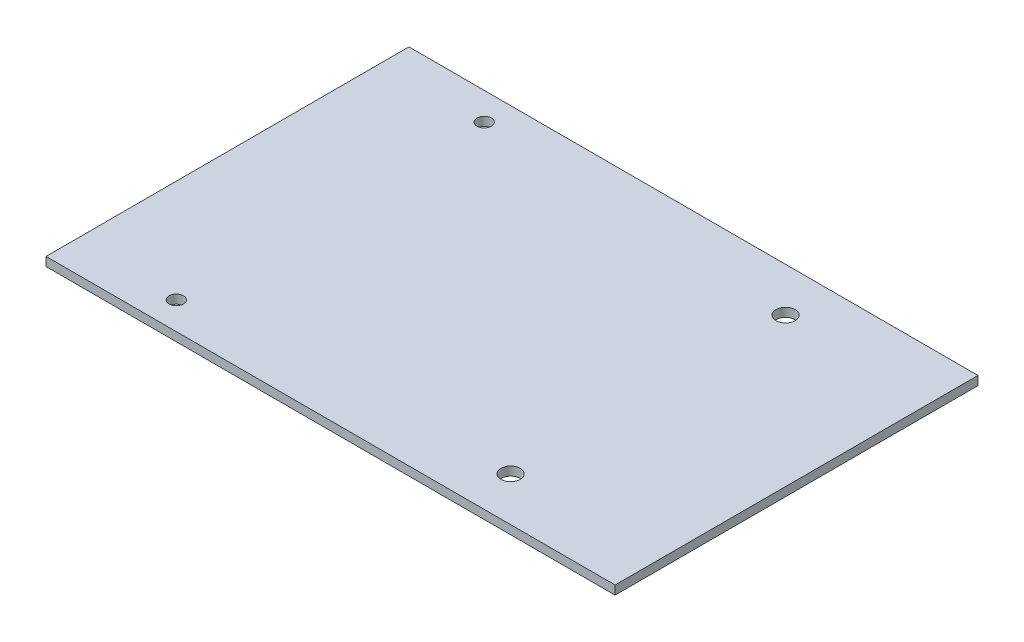
SolidWorks part; units mm, degrees
ref_plane "Front Plane" through (0, 0, 0) normal (0, 0, 1) x (1, 0, 0)
ref_plane "Top Plane" through (0, 0, 0) normal (0, 1, 0) x (1, 0, 0)
ref_plane "Right Plane" through (0, 0, 0) normal (1, 0, 0) x (0, 0, -1)
sketch "Sketch1" plane through (0, 0, 0) normal (0, 1, 0) x (1, 0, 0)
  line L1 (-51.75, -33) -> (51.75, -33)
  line L2 (-51.75, -33) -> (-51.75, 33)
  line L3 (-51.75, 33) -> (51.75, 33)
  line L4 (51.75, -33) -> (51.75, 33)
  line L5 (-51.75, -33) -> (51.75, 33) construction
  line L6 (-51.75, 33) -> (51.75, -33) construction
  point P0 (0, 0)
  dimension "D1" = 103.5
  dimension "D2" = 66
extrude "Boss-Extrude1" add sketch "Sketch1" along normal blind 1.6
sketch "Sketch2" plane through (0, 1.6, 0) normal (0, 1, 0) x (1, 0, 0)
  line L0 (-51.75, 33) -> (-51.75, -33) construction
  circle A6 centre (-16.77, 28) radius 3
  circle A7 centre (-16.77, -28) radius 3
  dimension "D1" = 34.98
  dimension "D2" = 56
  dimension "D3" = 28
extrude "Cut-Extrude1" [suppressed] cut sketch "Sketch2" against normal blind 1.6
sketch "Sketch3" plane through (0, 1.6, 0) normal (0, 1, 0) x (1, 0, 0)
  line L1 (-51.75, 33) -> (-51.75, -33) construction
  line L2 (0, 0) -> (-54.2874, 0) construction
  line L3 (51.75, 33) -> (-51.75, 33) construction
  circle A0 centre (-33.0523, 28) radius 1.3
  circle A6 centre (-33.0523, -28) radius 1.3
  dimension "D1" = 2.6
  dimension "D4" = 56
  dimension "D5" = 5
  dimension "D2" = 18.6977
extrude "Cut-Extrude2" cut sketch "Sketch3" against normal blind 10
sketch "Sketch4" plane through (0, 1.6, 0) normal (0, 1, 0) x (1, 0, 0)
  line L0 (51.75, -33) -> (51.75, 33) construction
  line L1 (51.75, 33) -> (-51.75, 33) construction
  line L3 (-51.75, -33) -> (51.75, -33) construction
  circle A0 centre (24.75, 25) radius 1.75
  circle A1 centre (24.75, -25) radius 1.75
  dimension "D1" = 3.5
  dimension "D2" = 27
  dimension "D3" = 8
  dimension "D4" = 8
extrude "Cut-Extrude3" cut sketch "Sketch4" against normal up to next
